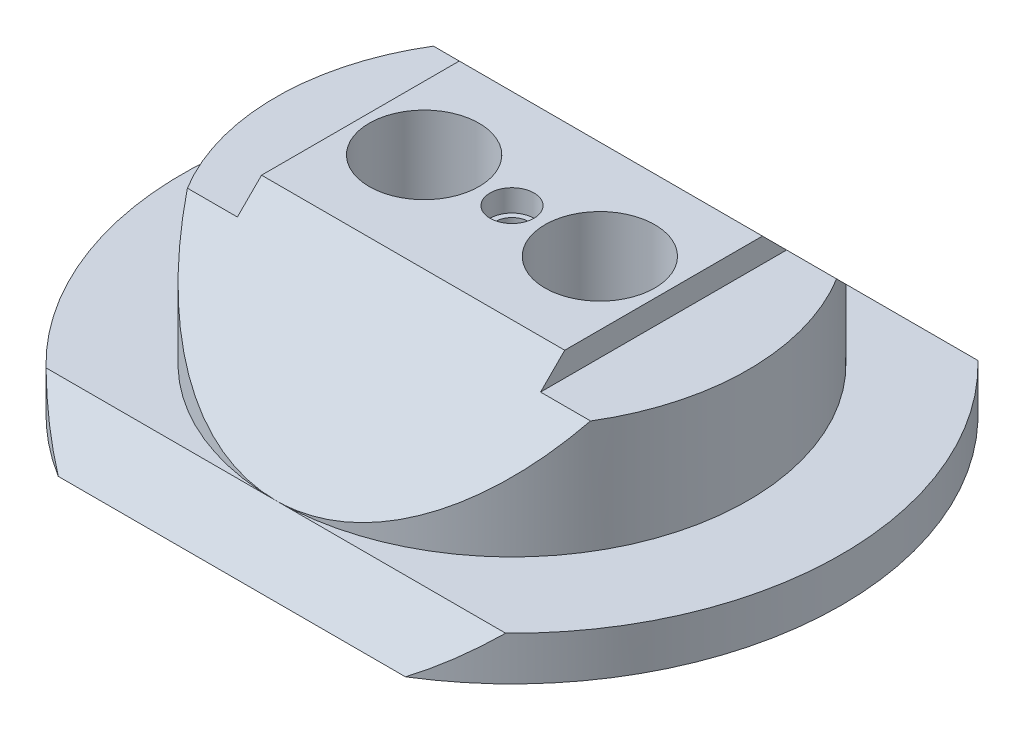
SolidWorks part; units mm, degrees
ref_plane "Front Plane" through (0, 0, 0) normal (0, 0, 1) x (1, 0, 0)
ref_plane "Top Plane" through (0, 0, 0) normal (0, 1, 0) x (1, 0, 0)
ref_plane "Right Plane" through (0, 0, 0) normal (1, 0, 0) x (0, 0, -1)
sketch "Sketch1" plane through (0, 0, 0) normal (0, 1, 0) x (1, 0, 0)
  circle A0 centre (0, 0) radius 30
extrude "Boss-Extrude1" add sketch "Sketch1" along normal blind 4
sketch "Sketch2" plane through (0, 0, 0) normal (1, 0, 0) x (0, 0, -1)
  line L0 (0, 4) -> (21.5, 4)
  line L1 (30, 4) -> (-30, 4) construction
  line L3 (0, 4) -> (-21.5, 4)
  line L5 (0, 4) -> (0, 19.5) construction
  line L6 (-9, 16.5) -> (-21.5, 4)
  line L7 (-9, 16.5) -> (9, 16.5)
  line L9 (9, 16.5) -> (21.5, 4)
  dimension "D1" = 12.5
  dimension "D2" = 45
  dimension "D3" = 21.5
  dimension "D4" = 21.5
  dimension "D5" = 45
sketch "Sketch3" plane through (0, 4, 0) normal (0, 1, 0) x (1, 0, 0)
  circle A0 centre (0, 0) radius 21.5
  dimension "D1" = 43
extrude "Boss-Extrude2" add sketch "Sketch2" along normal up to surface and the other way up to surface up to face at (0, 4, 30) other way up to face at (0, 4, 30)
ref_plane "Plane1" through (0, 12.75, -12.75) normal (0, 0.7071, -0.7071) x (1, 0, 0)
other "SurfaceCut1"
ref_plane "Plane2" through (0, 12.75, 12.75) normal (0, 0.7071, 0.7071) x (1, 0, 0)
other "SurfaceCut2"
extrude "Cut-Extrude2" cut sketch "Sketch3" against normal up to surface (12.5 mm away) flip side to cut contours A0
sketch "Sketch5" plane through (0, 0, 0) normal (0, -1, 0) x (-1, 0, 0)
  line L0 (0, 0) -> (0, -6)
  line L1 (0, -6) -> (-17.5, -6)
  line L2 (-17.5, -6) -> (-17.5, 6)
  line L3 (-17.5, 6) -> (17.5, 6)
  line L4 (17.5, 6) -> (17.5, -6)
  line L5 (17.5, -6) -> (0, -6)
  circle A0 centre (0, 0) radius 6
  circle A1 centre (0, 0) radius 3.5
  dimension "D1" = 12
  dimension "D2" = 7
  dimension "D3" = 12
  dimension "D4" = 6
  dimension "D5" = 35
  dimension "D6" = 17.5
extrude "Boss-Extrude3" add sketch "Sketch5" along normal blind 18 contours L1 L2 L3 L4 L5
sketch "Sketch6" plane through (0, 0, 0) normal (0, -1, 0) x (1, 0, 0)
  line L0 (0, 6) -> (0, 15) construction
  line L1 (-17.5, 6) -> (17.5, 6) construction
  line L2 (0, 15) -> (7, 15)
  line L3 (7, 15) -> (7, 6)
  line L4 (-17.5, 6) -> (17.5, 6) construction
  line L5 (7, 6) -> (-7, 6)
  line L6 (-7, 6) -> (-7, 15)
  line L7 (-7, 15) -> (0, 15)
  dimension "D1" = 14
  dimension "D2" = 9
extrude "Boss-Extrude4" add sketch "Sketch6" along normal blind 15 contours L7 L2 L3 L5 L6
sketch "Sketch7" plane through (0, 0, 0) normal (0, -1, 0) x (1, 0, 0)
  line L0 (0, -6) -> (0, -15) construction
  line L1 (17.5, -6) -> (-17.5, -6) construction
  line L2 (0, -15) -> (7, -15)
  line L3 (7, -15) -> (7, -6)
  line L4 (7, -6) -> (-7, -6)
  line L7 (-7, -6) -> (-7, -15)
  line L8 (-7, -15) -> (0, -15)
  dimension "D1" = 9
  dimension "D2" = 14
extrude "Boss-Extrude5" add sketch "Sketch7" along normal blind 15
sketch "Sketch8" plane through (0, 0, 0) normal (0, 0, 1) x (1, 0, 0)
  line L0 (0, 0) -> (12.5, 0) construction
  line L1 (12.5, 0) -> (12.5, -12.5) construction
  line L2 (12.5, -12.5) -> (-12.5, -12.5) construction
  line L3 (-12.5, -12.5) -> (-12.5, 0) construction
  line L4 (-12.5, 0) -> (0, 0) construction
  circle A0 centre (-12.5, -12.5) radius 2
  circle A1 centre (12.5, -12.5) radius 2
  dimension "D4" = 4
  dimension "D5" = 4
  dimension "D1" = 12.5
  dimension "D2" = 25
  dimension "D3" = 12.5
extrude "Cut-Extrude3" cut sketch "Sketch8" against normal through all both and the other way through all contours A0 | A1
ref_plane "Plane3" through (0, -18, 0) normal (0, -1, 0) x (-1, 0, 0)
ref_plane "Plane4" through (10.366, -9.6749, -8.0624) normal (0.6355, -0.5931, -0.4943) x (-0.3613, 0.3373, -0.8693)
ref_plane "Plane5" through (-10.366, -9.6749, -8.0624) normal (0.6355, 0.5931, 0.4943) x (0.3613, 0.3373, -0.8693)
ref_plane "Plane6" through (10.366, -9.6749, 8.0624) normal (-0.6355, 0.5931, -0.4943) x (-0.3613, 0.3373, 0.8693)
ref_plane "Plane7" through (-10.366, -9.6749, 8.0624) normal (0.6355, 0.5931, -0.4943) x (-0.3613, -0.3373, -0.8693)
ref_plane "Plane9" through (0, 0, 6) normal (0, 0, 1) x (1, 0, 0)
sketch "Sketch16" plane through (0, 0, 6) normal (0, 0, 1) x (1, 0, 0)
  line L0 (17.5, -18) -> (17.5, -14.5)
  line L1 (-6.6, -18) -> (6.6, -18) construction
  line L2 (17.5, -18) -> (17.5, 0) construction
  line L3 (17.5, -18) -> (14, -18)
  line L4 (17.5, -14.5) -> (14, -18)
  line L5 (-17.5, -18) -> (-14, -18)
  line L6 (-17.5, -18) -> (-17.5, 0) construction
  line L7 (-14, -18) -> (-17.5, -14.5)
  line L8 (-17.5, -14.5) -> (-17.5, -18)
  dimension "D2" = 3.5
extrude "Cut-Extrude8" cut sketch "Sketch16" against normal through all both and the other way through all
sketch "Sketch17" plane through (10.366, -9.6749, -8.0624) normal (0.6355, -0.5931, -0.4943) x (-0.3613, 0.3373, -0.8693)
  line L0 (-2.3725, -6.1896) -> (7.9806, -0.7067)
  line L1 (5.4512, -6.1896) -> (10.5101, 4.7762) construction
  line L2 (7.9806, -0.7067) -> (7.9806, -10.9658)
  line L3 (10.5101, -15.7421) -> (5.4512, -6.1896) construction
  line L4 (7.9806, -10.9658) -> (-2.3725, -6.1896)
extrude "Cut-Extrude9" cut sketch "Sketch17" along normal through all
sketch "Sketch19" plane through (-10.366, -9.6749, -8.0624) normal (0.6355, 0.5931, 0.4943) x (0.3613, 0.3373, -0.8693)
  line L0 (-2.3725, -6.1896) -> (7.9806, -10.9658)
  line L1 (7.9806, -10.9658) -> (7.9806, -0.7067)
  line L2 (5.4512, -6.1896) -> (10.5101, 4.7762) construction
  line L3 (7.9806, -0.7067) -> (-2.3725, -6.1896)
extrude "Cut-Extrude11" cut sketch "Sketch19" against normal blind 20 contours L3 L0 L1
sketch "Sketch20" plane through (-10.366, -9.6749, 8.0624) normal (0.6355, 0.5931, -0.4943) x (-0.3613, -0.3373, -0.8693)
  line L0 (2.3725, -6.1896) -> (-7.9806, -0.7067)
  line L1 (-5.4512, -6.1896) -> (-10.5101, 4.7762) construction
  line L2 (-7.9806, -0.7067) -> (-7.9806, -10.9658)
  line L3 (-5.4512, -6.1896) -> (-10.5101, -15.7421) construction
  line L4 (-7.9806, -10.9658) -> (2.3725, -6.1896)
extrude "Cut-Extrude12" cut sketch "Sketch20" against normal blind 20
sketch "Sketch21" plane through (10.366, -9.6749, 8.0624) normal (-0.6355, 0.5931, -0.4943) x (-0.3613, 0.3373, 0.8693)
  line L0 (-2.3725, -6.1896) -> (7.9806, -0.7067)
  line L1 (5.4512, -6.1896) -> (10.5101, 4.7762) construction
  line L2 (7.9806, -0.7067) -> (7.9806, -10.9658)
  line L3 (7.9806, -10.9658) -> (-2.3725, -6.1896)
extrude "Cut-Extrude13" cut sketch "Sketch21" against normal blind 20 contours L0 L2 L3
ref_plane "Plane10" through (0, 16.5, 0) normal (0, 1, 0) x (1, 0, 0)
sketch "Sketch25" plane through (0, 0, 0) normal (0, 0, 1) x (1, 0, 0)
  line L1 (-33.0377, 0) -> (33.0377, 0)
  line L2 (-33.0377, 0) -> (-33.0377, -20.1422)
  line L3 (-33.0377, -20.1422) -> (33.0377, -20.1422)
  line L4 (33.0377, 0) -> (33.0377, -20.1422)
  dimension "D1" = 20.1422
  dimension "D2" = 66.0754
extrude "Cut-Extrude14" cut sketch "Sketch25" along normal through all both and the other way through all
sketch "Sketch26" plane through (0, 16.5, 0) normal (0, 1, 0) x (1, 0, 0)
  line L0 (-9.075, 0) -> (9.075, 0) construction
  circle A0 centre (-8, 0) radius 5
  circle A2 centre (8, 0) radius 5
  dimension "D1" = 10
  dimension "D2" = 10
  dimension "D3" = 8
  dimension "D4" = 8
extrude "Cut-Extrude15" cut sketch "Sketch26" against normal blind 24
sketch "Sketch29" plane through (0, 0, 6) normal (0, 0, 1) x (1, 0, 0)
  line L0 (21.5, 4) -> (21.5, 16.5) construction
  line L1 (21.5, 14.3) -> (13.8, 14.3)
  line L2 (21.5, 14.3) -> (21.5, 16.5)
  line L3 (21.5, 16.5) -> (13.8, 16.5)
  line L4 (13.8, 14.3) -> (13.8, 16.5)
  line L5 (9.9, 16.5) -> (-9.9, 16.5) construction
  dimension "D1" = 2.2
  dimension "D2" = 7.7
extrude "Cut-Extrude17" cut sketch "Sketch29" against normal through all both and the other way through all
sketch "Sketch31" plane through (0, 0, 6) normal (0, 0, 1) x (1, 0, 0)
  line L0 (-21.5, 16.5) -> (-21.5, 4) construction
  line L1 (-21.5, 14.3) -> (-13.8, 14.3)
  line L2 (-21.5, 14.3) -> (-21.5, 16.5)
  line L3 (-21.5, 16.5) -> (-13.8, 16.5)
  line L4 (-13.8, 14.3) -> (-13.8, 16.5)
  line L5 (9.9, 16.5) -> (-9.9, 16.5) construction
  dimension "D1" = 2.2
  dimension "D2" = 7.7
extrude "Cut-Extrude18" cut sketch "Sketch31" against normal through all both and the other way through all
sketch "Sketch34" plane through (0, 0, 0) normal (0, -1, 0) x (1, 0, 0)
  circle A0 centre (0, 0) radius 1.5
  dimension "D1" = 3
extrude "Cut-Extrude21" cut sketch "Sketch34" against normal blind 20
sketch "Sketch35" plane through (0, 16.5, 0) normal (0, 1, 0) x (1, 0, 0)
  circle A0 centre (0, 0) radius 2
  dimension "D1" = 4
extrude "Cut-Extrude22" cut sketch "Sketch35" against normal blind 2
